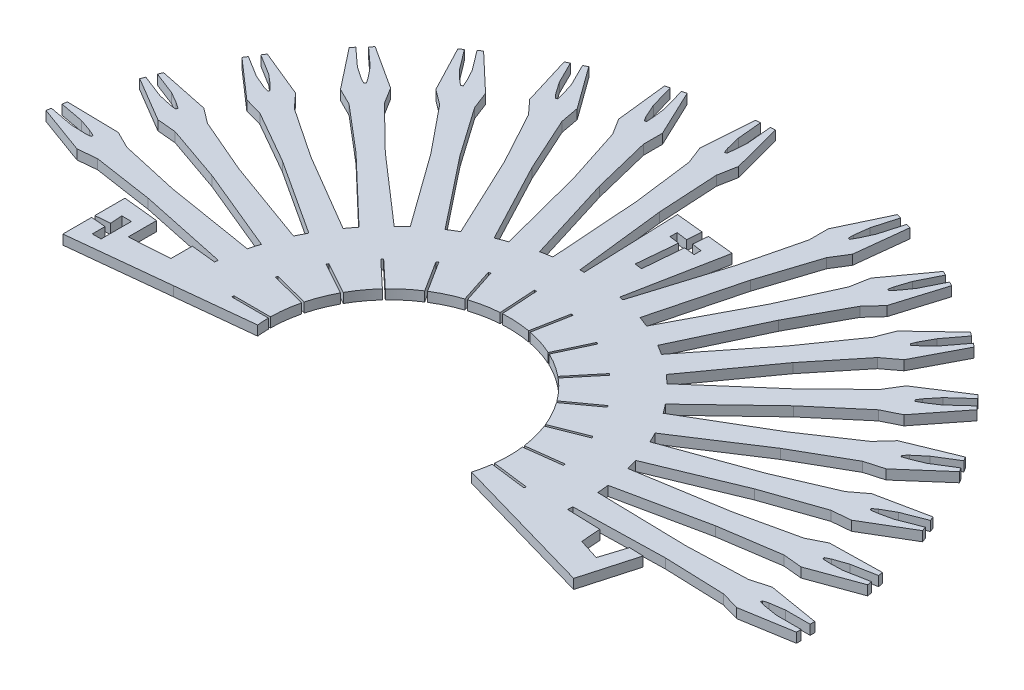
SolidWorks part; units mm, degrees
ref_plane "Front Plane" through (0, 0, 0) normal (0, 0, 1) x (1, 0, 0)
ref_plane "Top Plane" through (0, 0, 0) normal (0, 1, 0) x (1, 0, 0)
ref_plane "Right Plane" through (0, 0, 0) normal (1, 0, 0) x (0, 0, -1)
sketch "Sketch1" plane through (0, 0, 0) normal (0, 1, 0) x (1, 0, 0)
  line L5558 (72.849, 49.9) -> (72.743, 47.748) construction
  line L5559 (72.743, 47.748) -> (72.425, 45.667) construction
  line L5560 (72.425, 45.667) -> (71.896, 43.656) construction
  line L5561 (71.896, 43.656) -> (71.208, 41.716) construction
  line L5562 (71.208, 41.716) -> (70.309, 39.899) construction
  line L5563 (70.309, 39.899) -> (69.286, 38.171) construction
  line L5564 (69.286, 38.171) -> (66.71, 35.048) construction
  line L5565 (66.71, 35.048) -> (63.588, 32.491) construction
  line L5566 (63.588, 32.491) -> (61.877, 31.45) construction
  line L5567 (61.877, 31.45) -> (60.043, 30.551) construction
  line L5568 (60.043, 30.551) -> (58.12, 29.863) construction
  line L5569 (58.12, 29.863) -> (56.109, 29.333) construction
  line L5570 (56.109, 29.333) -> (54.01, 29.016) construction
  line L5571 (54.01, 29.016) -> (51.876, 28.91) construction
  line L5572 (51.876, 28.91) -> (49.724, 29.016) construction
  line L5573 (49.724, 29.016) -> (47.643, 29.333) construction
  line L5574 (47.643, 29.333) -> (45.632, 29.863) construction
  line L5575 (45.632, 29.863) -> (43.692, 30.551) construction
  line L5576 (43.692, 30.551) -> (41.839, 31.45) construction
  line L5577 (41.839, 31.45) -> (40.128, 32.491) construction
  line L5578 (40.128, 32.491) -> (37.006, 35.048) construction
  line L5579 (37.006, 35.048) -> (34.431, 38.171) construction
  line L5580 (34.431, 38.171) -> (33.408, 39.899) construction
  line L5581 (33.408, 39.899) -> (32.508, 41.716) construction
  line L5582 (32.508, 41.716) -> (31.821, 43.656) construction
  line L5583 (31.821, 43.656) -> (31.291, 45.667) construction
  line L5584 (31.291, 45.667) -> (30.974, 47.748) construction
  line L5585 (30.974, 47.748) -> (30.868, 49.9) construction
  line L5586 (30.868, 49.9) -> (30.974, 52.035) construction
  line L5587 (30.974, 52.035) -> (31.291, 54.134) construction
  line L5588 (31.291, 54.134) -> (31.821, 56.145) construction
  line L5589 (31.821, 56.145) -> (32.508, 58.067) construction
  line L5590 (32.508, 58.067) -> (33.408, 59.919) construction
  line L5591 (33.408, 59.919) -> (34.431, 61.648) construction
  line L5592 (34.431, 61.648) -> (37.006, 64.77) construction
  line L5593 (37.006, 64.77) -> (40.128, 67.328) construction
  line L5594 (40.128, 67.328) -> (41.839, 68.368) construction
  line L5595 (41.839, 68.368) -> (43.692, 69.268) construction
  line L5596 (43.692, 69.268) -> (45.632, 69.956) construction
  line L5597 (45.632, 69.956) -> (47.643, 70.485) construction
  line L5598 (47.643, 70.485) -> (49.724, 70.803) construction
  line L5599 (49.724, 70.803) -> (51.876, 70.908) construction
  line L5600 (51.876, 70.908) -> (54.01, 70.803) construction
  line L5601 (54.01, 70.803) -> (56.109, 70.485) construction
  line L5602 (56.109, 70.485) -> (58.12, 69.956) construction
  line L5603 (58.12, 69.956) -> (60.043, 69.268) construction
  line L5604 (60.043, 69.268) -> (61.877, 68.368) construction
  line L5605 (61.877, 68.368) -> (63.588, 67.328) construction
  line L5606 (63.588, 67.328) -> (66.71, 64.77) construction
  line L5607 (66.71, 64.77) -> (69.286, 61.648) construction
  line L5608 (69.286, 61.648) -> (70.309, 59.919) construction
  line L5609 (70.309, 59.919) -> (71.208, 58.067) construction
  line L5610 (71.208, 58.067) -> (71.896, 56.145) construction
  line L5611 (71.896, 56.145) -> (72.425, 54.134) construction
  line L5612 (72.425, 54.134) -> (72.743, 52.035) construction
  line L5613 (72.743, 52.035) -> (72.849, 49.9) construction
  line L5614 (62.054, 49.9) -> (61.842, 47.854) construction
  line L5615 (61.842, 47.854) -> (61.26, 45.932) construction
  line L5616 (61.26, 45.932) -> (60.307, 44.203) construction
  line L5617 (60.307, 44.203) -> (59.055, 42.704) construction
  line L5618 (59.055, 42.704) -> (57.556, 41.451) construction
  line L5619 (57.556, 41.451) -> (55.827, 40.499) construction
  line L5620 (55.827, 40.499) -> (53.922, 39.917) construction
  line L5621 (53.922, 39.917) -> (51.858, 39.705) construction
  line L5622 (51.858, 39.705) -> (49.795, 39.917) construction
  line L5623 (49.795, 39.917) -> (47.89, 40.499) construction
  line L5624 (47.89, 40.499) -> (46.143, 41.451) construction
  line L5625 (46.143, 41.451) -> (44.644, 42.704) construction
  line L5626 (44.644, 42.704) -> (43.392, 44.203) construction
  line L5627 (43.392, 44.203) -> (42.439, 45.932) construction
  line L5628 (42.439, 45.932) -> (41.857, 47.854) construction
  line L5629 (41.857, 47.854) -> (41.645, 49.9) construction
  line L5630 (41.645, 49.9) -> (41.857, 51.964) construction
  line L5631 (41.857, 51.964) -> (42.439, 53.869) construction
  line L5632 (42.439, 53.869) -> (43.392, 55.615) construction
  line L5633 (43.392, 55.615) -> (44.644, 57.115) construction
  line L5634 (44.644, 57.115) -> (46.143, 58.367) construction
  line L5635 (46.143, 58.367) -> (47.89, 59.32) construction
  line L5636 (47.89, 59.32) -> (49.795, 59.902) construction
  line L5637 (49.795, 59.902) -> (51.858, 60.113) construction
  line L5638 (51.858, 60.113) -> (53.922, 59.902) construction
  line L5639 (53.922, 59.902) -> (55.827, 59.32) construction
  line L5640 (55.827, 59.32) -> (57.556, 58.367) construction
  line L5641 (57.556, 58.367) -> (59.055, 57.115) construction
  line L5642 (59.055, 57.115) -> (60.307, 55.615) construction
  line L5643 (60.307, 55.615) -> (61.26, 53.869) construction
  line L5644 (61.26, 53.869) -> (61.842, 51.964) construction
  line L5645 (61.842, 51.964) -> (62.054, 49.9) construction
  line L5646 (30.85, 49.9) -> (51.841, 49.9) construction
  line L5647 (53.675, 70.82) -> (51.841, 49.9) construction
  line L5648 (72.531, 46.249) -> (51.858, 49.9) construction
  line L5649 (72.796, 48.436) -> (51.841, 49.9) construction
  line L5650 (51.488, 70.891) -> (51.841, 49.9) construction
  line L5651 (55.862, 70.52) -> (51.858, 49.9) construction
  line L5652 (30.956, 47.696) -> (51.841, 49.9) construction
  line L5653 (30.956, 52.088) -> (51.841, 49.9) construction
  line L5654 (72.037, 44.115) -> (51.841, 49.9) construction
  line L5655 (62.406, 49.177) -> (67.045, 49.424) construction
  line L5656 (67.345, 50.077) -> (67.469, 50.324) construction
  line L5657 (67.469, 50.324) -> (67.68, 50.377) construction
  line L5658 (67.68, 50.377) -> (67.892, 50.271) construction
  line L5659 (67.892, 50.271) -> (67.945, 50.059) construction
  line L5660 (67.945, 50.059) -> (67.839, 49.848) construction
  line L5661 (67.839, 49.848) -> (67.628, 49.759) construction
  line L5662 (67.628, 49.759) -> (67.416, 49.865) construction
  line L5663 (67.416, 49.865) -> (67.345, 50.077) construction
  line L5664 (69.832, 50.094) -> (69.938, 50.341) construction
  line L5665 (69.938, 50.341) -> (70.168, 50.394) construction
  line L5666 (70.168, 50.394) -> (70.379, 50.288) construction
  line L5667 (70.379, 50.288) -> (70.432, 50.077) construction
  line L5668 (70.432, 50.077) -> (70.326, 49.865) construction
  line L5669 (70.326, 49.865) -> (70.115, 49.777) construction
  line L5670 (70.115, 49.777) -> (69.903, 49.883) construction
  line L5671 (69.903, 49.883) -> (69.832, 50.094) construction
  line L5672 (67.045, 49.424) -> (71.702, 49.477) construction
  line L5673 (71.914, 50.094) -> (71.702, 49.477) construction
  line L5674 (62.389, 50.835) -> (67.045, 50.659) construction
  line L5675 (67.045, 50.659) -> (71.702, 50.712) construction
  line L5676 (71.914, 50.094) -> (71.702, 50.712) construction
  line L5677 (70.132, 50.377) -> (67.645, 50.359) construction
  line L5678 (70.15, 49.777) -> (67.645, 49.742) construction
  line L5679 (57.344, 49.953) -> (51.841, 49.9) construction
  line L5680 (62.353, 51.118) -> (66.887, 52.229) construction
  line L5681 (67.045, 52.917) -> (67.345, 53.252) construction
  line L5682 (67.345, 53.252) -> (67.557, 53.199) construction
  line L5683 (67.557, 53.199) -> (67.663, 52.987) construction
  line L5684 (67.663, 52.987) -> (67.61, 52.776) construction
  line L5685 (67.61, 52.776) -> (67.398, 52.652) construction
  line L5686 (67.398, 52.652) -> (67.187, 52.723) construction
  line L5687 (67.187, 52.723) -> (67.045, 52.917) construction
  line L5688 (69.48, 53.393) -> (69.779, 53.746) construction
  line L5689 (69.779, 53.746) -> (69.991, 53.693) construction
  line L5690 (69.991, 53.693) -> (70.097, 53.481) construction
  line L5691 (70.097, 53.481) -> (70.044, 53.269) construction
  line L5692 (70.044, 53.269) -> (69.832, 53.128) construction
  line L5693 (69.832, 53.128) -> (69.621, 53.217) construction
  line L5694 (69.621, 53.217) -> (69.48, 53.393) construction
  line L5695 (66.887, 52.229) -> (71.455, 53.128) construction
  line L5696 (71.543, 53.763) -> (71.455, 53.128) construction
  line L5697 (62.036, 52.758) -> (66.64, 53.428) construction
  line L5698 (66.64, 53.428) -> (71.208, 54.328) construction
  line L5699 (71.543, 53.781) -> (71.208, 54.328) construction
  line L5700 (69.744, 53.728) -> (67.292, 53.252) construction
  line L5701 (69.85, 53.128) -> (67.416, 52.634) construction
  line L5702 (57.238, 50.959) -> (51.841, 49.9) construction
  line L5703 (61.965, 53.023) -> (66.199, 54.945) construction
  line L5704 (66.234, 55.651) -> (66.446, 56.039) construction
  line L5705 (66.446, 56.039) -> (66.693, 56.021) construction
  line L5706 (66.693, 56.021) -> (66.851, 55.827) construction
  line L5707 (66.851, 55.827) -> (66.64, 55.457) construction
  line L5708 (66.64, 55.457) -> (66.393, 55.492) construction
  line L5709 (66.393, 55.492) -> (66.234, 55.651) construction
  line L5710 (68.545, 56.568) -> (68.756, 56.956) construction
  line L5711 (68.756, 56.956) -> (69.003, 56.938) construction
  line L5712 (69.003, 56.938) -> (69.162, 56.744) construction
  line L5713 (69.162, 56.744) -> (68.95, 56.374) construction
  line L5714 (68.95, 56.374) -> (68.703, 56.409) construction
  line L5715 (68.703, 56.409) -> (68.545, 56.568) construction
  line L5716 (66.199, 54.945) -> (70.52, 56.656) construction
  line L5717 (70.503, 57.309) -> (70.52, 56.656) construction
  line L5718 (61.348, 54.575) -> (65.74, 56.092) construction
  line L5719 (65.74, 56.092) -> (70.079, 57.803) construction
  line L5720 (70.503, 57.309) -> (70.079, 57.803) construction
  line L5721 (68.739, 56.938) -> (66.41, 56.021) construction
  line L5722 (68.968, 56.374) -> (66.64, 55.439) construction
  line L5723 (56.956, 51.929) -> (51.841, 49.9) construction
  line L5724 (61.225, 54.822) -> (65.035, 57.485) construction
  line L5725 (64.946, 58.191) -> (65.07, 58.614) construction
  line L5726 (65.07, 58.614) -> (65.317, 58.632) construction
  line L5727 (65.317, 58.632) -> (65.493, 58.473) construction
  line L5728 (65.493, 58.473) -> (65.528, 58.244) construction
  line L5729 (65.528, 58.244) -> (65.37, 58.05) construction
  line L5730 (65.37, 58.05) -> (64.946, 58.191) construction
  line L5731 (67.045, 59.514) -> (67.169, 59.937) construction
  line L5732 (67.169, 59.937) -> (67.416, 59.955) construction
  line L5733 (67.416, 59.955) -> (67.592, 59.796) construction
  line L5734 (67.592, 59.796) -> (67.628, 59.567) construction
  line L5735 (67.628, 59.567) -> (67.469, 59.373) construction
  line L5736 (67.469, 59.373) -> (67.045, 59.514) construction
  line L5737 (65.035, 57.485) -> (68.968, 59.972) construction
  line L5738 (68.827, 60.607) -> (68.968, 59.972) construction
  line L5739 (60.325, 56.233) -> (64.382, 58.526) construction
  line L5740 (64.382, 58.526) -> (68.315, 61.013) construction
  line L5741 (68.827, 60.607) -> (68.315, 61.013) construction
  line L5742 (67.169, 59.919) -> (65.052, 58.579) construction
  line L5743 (67.486, 59.39) -> (65.37, 58.067) construction
  line L5744 (56.497, 52.828) -> (51.858, 49.9) construction
  line L5745 (60.149, 56.444) -> (63.429, 59.761) construction
  line L5746 (63.2, 60.448) -> (63.147, 60.678) construction
  line L5747 (63.147, 60.678) -> (63.288, 60.889) construction
  line L5748 (63.288, 60.889) -> (63.5, 60.942) construction
  line L5749 (63.5, 60.942) -> (63.712, 60.837) construction
  line L5750 (63.712, 60.837) -> (63.765, 60.607) construction
  line L5751 (63.765, 60.607) -> (63.659, 60.396) construction
  line L5752 (63.659, 60.396) -> (63.412, 60.343) construction
  line L5753 (63.412, 60.343) -> (63.2, 60.448) construction
  line L5754 (65.017, 62.124) -> (64.964, 62.371) construction
  line L5755 (64.964, 62.371) -> (65.105, 62.583) construction
  line L5756 (65.105, 62.583) -> (65.317, 62.636) construction
  line L5757 (65.317, 62.636) -> (65.528, 62.53) construction
  line L5758 (65.528, 62.53) -> (65.581, 62.283) construction
  line L5759 (65.581, 62.283) -> (65.476, 62.071) construction
  line L5760 (65.476, 62.071) -> (65.229, 62.018) construction
  line L5761 (65.229, 62.018) -> (65.017, 62.124) construction
  line L5762 (63.429, 59.761) -> (66.834, 62.936) construction
  line L5763 (66.587, 63.535) -> (66.834, 62.936) construction
  line L5764 (59.02, 57.679) -> (62.583, 60.678) construction
  line L5765 (62.583, 60.678) -> (66.005, 63.835) construction
  line L5766 (66.587, 63.535) -> (66.005, 63.835) construction
  line L5767 (65.07, 62.548) -> (63.235, 60.854) construction
  line L5768 (65.493, 62.089) -> (63.659, 60.396) construction
  line L5769 (55.88, 53.622) -> (51.841, 49.9) construction
  line L5770 (58.808, 57.873) -> (61.419, 61.718) construction
  line L5771 (61.083, 62.353) -> (60.995, 62.583) construction
  line L5772 (60.995, 62.583) -> (61.083, 62.794) construction
  line L5773 (61.083, 62.794) -> (61.295, 62.9) construction
  line L5774 (61.295, 62.9) -> (61.507, 62.83) construction
  line L5775 (61.507, 62.83) -> (61.613, 62.618) construction
  line L5776 (61.613, 62.618) -> (61.524, 62.371) construction
  line L5777 (61.524, 62.371) -> (61.313, 62.301) construction
  line L5778 (61.313, 62.301) -> (61.083, 62.353) construction
  line L5779 (62.565, 64.329) -> (62.477, 64.576) construction
  line L5780 (62.477, 64.576) -> (62.565, 64.788) construction
  line L5781 (62.565, 64.788) -> (62.777, 64.893) construction
  line L5782 (62.777, 64.893) -> (62.988, 64.805) construction
  line L5783 (62.988, 64.805) -> (63.094, 64.594) construction
  line L5784 (63.094, 64.594) -> (63.006, 64.364) construction
  line L5785 (63.006, 64.364) -> (62.794, 64.276) construction
  line L5786 (62.794, 64.276) -> (62.565, 64.329) construction
  line L5787 (61.419, 61.718) -> (64.206, 65.458) construction
  line L5788 (63.835, 66.005) -> (64.206, 65.458) construction
  line L5789 (57.485, 58.861) -> (60.431, 62.459) construction
  line L5790 (60.431, 62.459) -> (63.2, 66.199) construction
  line L5791 (63.835, 66.005) -> (63.2, 66.199) construction
  line L5792 (62.53, 64.752) -> (61.031, 62.759) construction
  line L5793 (63.024, 64.382) -> (61.524, 62.389) construction
  line L5794 (55.122, 54.31) -> (51.858, 49.9) construction
  line L5795 (57.238, 59.002) -> (59.09, 63.271) construction
  line L5796 (58.649, 63.835) -> (58.508, 64.047) construction
  line L5797 (58.508, 64.047) -> (58.561, 64.258) construction
  line L5798 (58.561, 64.258) -> (58.755, 64.417) construction
  line L5799 (58.755, 64.417) -> (58.967, 64.364) construction
  line L5800 (58.967, 64.364) -> (59.126, 64.17) construction
  line L5801 (59.126, 64.17) -> (59.073, 63.941) construction
  line L5802 (59.073, 63.941) -> (58.879, 63.8) construction
  line L5803 (58.879, 63.8) -> (58.649, 63.835) construction
  line L5804 (59.743, 66.058) -> (59.602, 66.269) construction
  line L5805 (59.602, 66.269) -> (59.655, 66.481) construction
  line L5806 (59.655, 66.481) -> (59.849, 66.604) construction
  line L5807 (59.849, 66.604) -> (60.06, 66.587) construction
  line L5808 (60.06, 66.587) -> (60.219, 66.393) construction
  line L5809 (60.219, 66.393) -> (60.166, 66.163) construction
  line L5810 (60.166, 66.163) -> (59.972, 66.022) construction
  line L5811 (59.972, 66.022) -> (59.743, 66.058) construction
  line L5812 (59.09, 63.271) -> (61.136, 67.451) construction
  line L5813 (60.695, 67.927) -> (61.136, 67.451) construction
  line L5814 (55.739, 59.743) -> (57.979, 63.818) construction
  line L5815 (57.979, 63.818) -> (60.025, 67.998) construction
  line L5816 (60.678, 67.927) -> (60.025, 67.998) construction
  line L5817 (59.619, 66.463) -> (58.526, 64.223) construction
  line L5818 (60.184, 66.181) -> (59.073, 63.941) construction
  line L5819 (54.257, 54.822) -> (51.841, 49.9) construction
  line L5820 (55.457, 59.849) -> (56.497, 64.382) construction
  line L5821 (55.951, 64.841) -> (55.792, 64.999) construction
  line L5822 (55.792, 64.999) -> (55.792, 65.246) construction
  line L5823 (55.792, 65.246) -> (55.951, 65.423) construction
  line L5824 (55.951, 65.423) -> (56.18, 65.423) construction
  line L5825 (56.18, 65.423) -> (56.339, 65.264) construction
  line L5826 (56.339, 65.264) -> (56.339, 65.035) construction
  line L5827 (56.339, 65.035) -> (56.18, 64.876) construction
  line L5828 (56.18, 64.876) -> (55.951, 64.841) construction
  line L5829 (56.603, 67.239) -> (56.444, 67.398) construction
  line L5830 (56.444, 67.398) -> (56.444, 67.628) construction
  line L5831 (56.444, 67.628) -> (56.603, 67.822) construction
  line L5832 (56.603, 67.822) -> (56.85, 67.822) construction
  line L5833 (56.85, 67.822) -> (57.009, 67.663) construction
  line L5834 (57.009, 67.663) -> (57.009, 67.416) construction
  line L5835 (57.009, 67.416) -> (56.85, 67.257) construction
  line L5836 (56.85, 67.257) -> (56.603, 67.239) construction
  line L5837 (56.497, 64.382) -> (57.732, 68.88) construction
  line L5838 (57.203, 69.25) -> (57.732, 68.88) construction
  line L5839 (53.852, 60.29) -> (55.298, 64.717) construction
  line L5840 (55.298, 64.717) -> (56.533, 69.197) construction
  line L5841 (57.185, 69.25) -> (56.533, 69.197) construction
  line L5842 (56.427, 67.61) -> (55.757, 65.211) construction
  line L5843 (57.009, 67.451) -> (56.356, 65.035) construction
  line L5844 (53.305, 55.192) -> (51.841, 49.9) construction
  line L5845 (51.664, 60.484) -> (50.994, 65.088) construction
  line L5846 (50.324, 65.317) -> (50.112, 65.423) construction
  line L5847 (50.112, 65.423) -> (50.024, 65.634) construction
  line L5848 (50.024, 65.634) -> (50.112, 65.846) construction
  line L5849 (50.112, 65.846) -> (50.324, 65.952) construction
  line L5850 (50.324, 65.952) -> (50.553, 65.846) construction
  line L5851 (50.553, 65.846) -> (50.641, 65.634) construction
  line L5852 (50.641, 65.634) -> (50.553, 65.423) construction
  line L5853 (50.553, 65.423) -> (50.324, 65.317) construction
  line L5854 (50.077, 67.786) -> (49.865, 67.892) construction
  line L5855 (49.865, 67.892) -> (49.795, 68.104) construction
  line L5856 (49.795, 68.104) -> (49.865, 68.315) construction
  line L5857 (49.865, 68.315) -> (50.077, 68.421) construction
  line L5858 (50.077, 68.421) -> (50.324, 68.315) construction
  line L5859 (50.324, 68.315) -> (50.394, 68.104) construction
  line L5860 (50.394, 68.104) -> (50.324, 67.892) construction
  line L5861 (50.324, 67.892) -> (50.077, 67.786) construction
  line L5862 (50.994, 65.088) -> (50.535, 69.727) construction
  line L5863 (49.918, 69.885) -> (50.535, 69.727) construction
  line L5864 (50.006, 60.325) -> (49.759, 64.964) construction
  line L5865 (49.759, 64.964) -> (49.318, 69.603) construction
  line L5866 (49.9, 69.885) -> (49.318, 69.603) construction
  line L5867 (49.777, 68.068) -> (50.024, 65.599) construction
  line L5868 (50.377, 68.139) -> (50.624, 65.652) construction
  line L5869 (51.312, 55.368) -> (51.858, 49.9) construction
  line L5870 (49.724, 60.272) -> (48.225, 64.664) construction
  line L5871 (47.519, 64.788) -> (47.308, 64.841) construction
  line L5872 (47.308, 64.841) -> (47.184, 65.052) construction
  line L5873 (47.184, 65.052) -> (47.237, 65.264) construction
  line L5874 (47.237, 65.264) -> (47.413, 65.387) construction
  line L5875 (47.413, 65.387) -> (47.66, 65.334) construction
  line L5876 (47.66, 65.334) -> (47.784, 65.158) construction
  line L5877 (47.784, 65.158) -> (47.731, 64.946) construction
  line L5878 (47.731, 64.946) -> (47.519, 64.788) construction
  line L5879 (46.831, 67.169) -> (46.62, 67.222) construction
  line L5880 (46.62, 67.222) -> (46.496, 67.433) construction
  line L5881 (46.496, 67.433) -> (46.549, 67.645) construction
  line L5882 (46.549, 67.645) -> (46.725, 67.769) construction
  line L5883 (46.725, 67.769) -> (46.972, 67.716) construction
  line L5884 (46.972, 67.716) -> (47.096, 67.539) construction
  line L5885 (47.096, 67.539) -> (47.043, 67.328) construction
  line L5886 (47.043, 67.328) -> (46.831, 67.169) construction
  line L5887 (48.225, 64.664) -> (46.937, 69.144) construction
  line L5888 (46.284, 69.18) -> (46.937, 69.144) construction
  line L5889 (48.119, 59.796) -> (47.043, 64.329) construction
  line L5890 (47.043, 64.329) -> (45.738, 68.809) construction
  line L5891 (46.267, 69.18) -> (45.738, 68.792) construction
  line L5892 (46.478, 67.381) -> (47.166, 64.982) construction
  line L5893 (47.061, 67.557) -> (47.766, 65.158) construction
  line L5894 (50.324, 55.174) -> (51.841, 49.9) construction
  line L5895 (47.854, 59.708) -> (45.579, 63.747) construction
  line L5896 (44.873, 63.729) -> (44.662, 63.765) construction
  line L5897 (44.662, 63.765) -> (44.503, 63.923) construction
  line L5898 (44.503, 63.923) -> (44.503, 64.153) construction
  line L5899 (44.503, 64.153) -> (44.662, 64.311) construction
  line L5900 (44.662, 64.311) -> (44.891, 64.311) construction
  line L5901 (44.891, 64.311) -> (45.05, 64.135) construction
  line L5902 (45.05, 64.135) -> (45.05, 63.923) construction
  line L5903 (45.05, 63.923) -> (44.873, 63.729) construction
  line L5904 (43.762, 65.952) -> (43.55, 65.969) construction
  line L5905 (43.55, 65.969) -> (43.356, 66.128) construction
  line L5906 (43.356, 66.128) -> (43.392, 66.375) construction
  line L5907 (43.392, 66.375) -> (43.55, 66.534) construction
  line L5908 (43.55, 66.534) -> (43.78, 66.534) construction
  line L5909 (43.78, 66.534) -> (43.938, 66.34) construction
  line L5910 (43.938, 66.34) -> (43.938, 66.128) construction
  line L5911 (43.938, 66.128) -> (43.762, 65.952) construction
  line L5912 (45.579, 63.747) -> (43.498, 67.91) construction
  line L5913 (42.845, 67.839) -> (43.498, 67.91) construction
  line L5914 (46.373, 58.949) -> (44.485, 63.2) construction
  line L5915 (44.485, 63.2) -> (42.386, 67.363) construction
  line L5916 (42.827, 67.839) -> (42.386, 67.363) construction
  line L5917 (43.374, 66.111) -> (44.485, 63.87) construction
  line L5918 (43.921, 66.393) -> (45.032, 64.153) construction
  line L5919 (49.389, 54.804) -> (51.841, 49.9) construction
  line L5920 (46.126, 58.808) -> (43.145, 62.371) construction
  line L5921 (42.457, 62.23) -> (42.245, 62.195) construction
  line L5922 (42.245, 62.195) -> (42.051, 62.336) construction
  line L5923 (42.051, 62.336) -> (41.998, 62.565) construction
  line L5924 (41.998, 62.565) -> (42.139, 62.759) construction
  line L5925 (42.139, 62.759) -> (42.369, 62.777) construction
  line L5926 (42.369, 62.777) -> (42.563, 62.653) construction
  line L5927 (42.563, 62.653) -> (42.58, 62.442) construction
  line L5928 (42.58, 62.442) -> (42.457, 62.23) construction
  line L5929 (40.958, 64.188) -> (40.746, 64.17) construction
  line L5930 (40.746, 64.17) -> (40.552, 64.294) construction
  line L5931 (40.552, 64.294) -> (40.499, 64.541) construction
  line L5932 (40.499, 64.541) -> (40.64, 64.717) construction
  line L5933 (40.64, 64.717) -> (40.869, 64.752) construction
  line L5934 (40.869, 64.752) -> (41.063, 64.611) construction
  line L5935 (41.063, 64.611) -> (41.081, 64.4) construction
  line L5936 (41.081, 64.4) -> (40.958, 64.188) construction
  line L5937 (43.145, 62.371) -> (40.323, 66.075) construction
  line L5938 (39.705, 65.881) -> (40.323, 66.075) construction
  line L5939 (44.803, 57.803) -> (42.157, 61.63) construction
  line L5940 (42.157, 61.63) -> (39.352, 65.334) construction
  line L5941 (39.705, 65.881) -> (39.352, 65.334) construction
  line L5942 (40.534, 64.276) -> (42.051, 62.301) construction
  line L5943 (41.028, 64.647) -> (42.545, 62.671) construction
  line L5944 (48.525, 54.275) -> (51.858, 49.9) construction
  line L5945 (44.591, 57.609) -> (41.01, 60.572) construction
  line L5946 (40.358, 60.29) -> (40.146, 60.219) construction
  line L5947 (40.146, 60.219) -> (39.934, 60.325) construction
  line L5948 (39.934, 60.325) -> (39.846, 60.537) construction
  line L5949 (39.846, 60.537) -> (39.952, 60.748) construction
  line L5950 (39.952, 60.748) -> (40.164, 60.819) construction
  line L5951 (40.164, 60.819) -> (40.375, 60.748) construction
  line L5952 (40.375, 60.748) -> (40.464, 60.537) construction
  line L5953 (40.464, 60.537) -> (40.358, 60.29) construction
  line L5954 (38.523, 61.965) -> (38.312, 61.877) construction
  line L5955 (38.312, 61.877) -> (38.1, 61.983) construction
  line L5956 (38.1, 61.983) -> (38.012, 62.195) construction
  line L5957 (38.012, 62.195) -> (38.118, 62.406) construction
  line L5958 (38.118, 62.406) -> (38.329, 62.495) construction
  line L5959 (38.329, 62.495) -> (38.541, 62.406) construction
  line L5960 (38.541, 62.406) -> (38.629, 62.195) construction
  line L5961 (38.629, 62.195) -> (38.523, 61.965) construction
  line L5962 (41.01, 60.572) -> (37.553, 63.694) construction
  line L5963 (36.989, 63.394) -> (37.553, 63.694) construction
  line L5964 (43.48, 56.374) -> (40.181, 59.655) construction
  line L5965 (40.181, 59.655) -> (36.724, 62.777) construction
  line L5966 (36.971, 63.377) -> (36.724, 62.777) construction
  line L5967 (38.1, 61.965) -> (39.952, 60.29) construction
  line L5968 (38.506, 62.424) -> (40.358, 60.748) construction
  line L5969 (47.784, 53.587) -> (51.841, 49.9) construction
  line L5970 (43.303, 56.145) -> (39.247, 58.402) construction
  line L5971 (38.647, 58.014) -> (38.453, 57.908) construction
  line L5972 (38.453, 57.908) -> (38.223, 57.961) construction
  line L5973 (38.223, 57.961) -> (38.118, 58.173) construction
  line L5974 (38.118, 58.173) -> (38.171, 58.385) construction
  line L5975 (38.171, 58.385) -> (38.594, 58.455) construction
  line L5976 (38.594, 58.455) -> (38.7, 58.244) construction
  line L5977 (38.7, 58.244) -> (38.647, 58.014) construction
  line L5978 (36.53, 59.32) -> (36.354, 59.214) construction
  line L5979 (36.354, 59.214) -> (36.107, 59.267) construction
  line L5980 (36.107, 59.267) -> (36.001, 59.478) construction
  line L5981 (36.001, 59.478) -> (36.054, 59.69) construction
  line L5982 (36.054, 59.69) -> (36.477, 59.761) construction
  line L5983 (36.477, 59.761) -> (36.583, 59.549) construction
  line L5984 (36.583, 59.549) -> (36.53, 59.32) construction
  line L5985 (39.247, 58.402) -> (35.278, 60.854) construction
  line L5986 (34.766, 60.448) -> (35.278, 60.837) construction
  line L5987 (42.439, 54.733) -> (38.594, 57.344) construction
  line L5988 (38.594, 57.344) -> (34.625, 59.796) construction
  line L5989 (34.766, 60.431) -> (34.625, 59.796) construction
  line L5990 (36.124, 59.249) -> (38.241, 57.926) construction
  line L5991 (36.442, 59.761) -> (38.559, 58.455) construction
  line L5992 (47.184, 52.776) -> (51.841, 49.9) construction
  line L5993 (42.316, 54.469) -> (37.888, 55.951) construction
  line L5994 (37.377, 55.457) -> (37.218, 55.316) construction
  line L5995 (37.218, 55.316) -> (36.989, 55.316) construction
  line L5996 (36.989, 55.316) -> (36.83, 55.51) construction
  line L5997 (36.83, 55.51) -> (36.848, 55.739) construction
  line L5998 (36.848, 55.739) -> (37.006, 55.898) construction
  line L5999 (37.006, 55.898) -> (37.253, 55.88) construction
  line L6000 (37.253, 55.88) -> (37.412, 55.686) construction
  line L6001 (37.412, 55.686) -> (37.377, 55.457) construction
  line L6002 (35.066, 56.356) -> (34.907, 56.215) construction
  line L6003 (34.907, 56.215) -> (34.678, 56.215) construction
  line L6004 (34.678, 56.215) -> (34.519, 56.409) construction
  line L6005 (34.519, 56.409) -> (34.537, 56.638) construction
  line L6006 (34.537, 56.638) -> (34.696, 56.797) construction
  line L6007 (34.696, 56.797) -> (34.943, 56.78) construction
  line L6008 (34.943, 56.78) -> (35.101, 56.586) construction
  line L6009 (35.101, 56.586) -> (35.066, 56.356) construction
  line L6010 (37.888, 55.951) -> (33.549, 57.626) construction
  line L6011 (33.126, 57.132) -> (33.549, 57.626) construction
  line L6012 (41.716, 52.917) -> (37.447, 54.804) construction
  line L6013 (37.447, 54.804) -> (33.108, 56.48) construction
  line L6014 (33.126, 57.132) -> (33.108, 56.48) construction
  line L6015 (34.678, 56.198) -> (37.006, 55.298) construction
  line L6016 (34.89, 56.78) -> (37.218, 55.88) construction
  line L6017 (46.725, 51.876) -> (51.858, 49.9) construction
  line L6018 (41.628, 52.652) -> (37.024, 53.287) construction
  line L6019 (36.601, 52.705) -> (36.477, 52.529) construction
  line L6020 (36.477, 52.529) -> (36.23, 52.493) construction
  line L6021 (36.23, 52.493) -> (36.054, 52.652) construction
  line L6022 (36.054, 52.652) -> (36.019, 52.899) construction
  line L6023 (36.019, 52.899) -> (36.389, 53.111) construction
  line L6024 (36.389, 53.111) -> (36.583, 52.952) construction
  line L6025 (36.583, 52.952) -> (36.601, 52.705) construction
  line L6026 (34.167, 53.164) -> (34.043, 52.987) construction
  line L6027 (34.043, 52.987) -> (33.796, 52.952) construction
  line L6028 (33.796, 52.952) -> (33.62, 53.111) construction
  line L6029 (33.62, 53.111) -> (33.584, 53.358) construction
  line L6030 (33.584, 53.358) -> (33.955, 53.569) construction
  line L6031 (33.955, 53.569) -> (34.149, 53.411) construction
  line L6032 (34.149, 53.411) -> (34.167, 53.164) construction
  line L6033 (37.024, 53.287) -> (32.438, 54.134) construction
  line L6034 (32.12, 53.587) -> (32.438, 54.134) construction
  line L6035 (41.328, 51.012) -> (36.795, 52.07) construction
  line L6036 (36.795, 52.07) -> (32.226, 52.934) construction
  line L6037 (32.12, 53.569) -> (32.226, 52.934) construction
  line L6038 (33.814, 52.952) -> (36.266, 52.493) construction
  line L6039 (33.92, 53.552) -> (36.371, 53.093) construction
  line L6040 (46.461, 50.906) -> (51.858, 49.9) construction
  line L6041 (57.856, 49.9) -> (57.714, 48.683) construction
  line L6042 (57.714, 48.683) -> (57.379, 47.572) construction
  line L6043 (57.379, 47.572) -> (56.815, 46.567) construction
  line L6044 (56.815, 46.567) -> (56.109, 45.667) construction
  line L6045 (56.109, 45.667) -> (55.21, 44.944) construction
  line L6046 (55.21, 44.944) -> (54.204, 44.397) construction
  line L6047 (54.204, 44.397) -> (53.093, 44.044) construction
  line L6048 (53.093, 44.044) -> (51.876, 43.921) construction
  line L6049 (51.876, 43.921) -> (50.659, 44.044) construction
  line L6050 (50.659, 44.044) -> (49.512, 44.397) construction
  line L6051 (49.512, 44.397) -> (48.507, 44.944) construction
  line L6052 (48.507, 44.944) -> (47.607, 45.667) construction
  line L6053 (47.607, 45.667) -> (46.902, 46.567) construction
  line L6054 (46.902, 46.567) -> (46.337, 47.572) construction
  line L6055 (46.337, 47.572) -> (46.002, 48.683) construction
  line L6056 (46.002, 48.683) -> (45.861, 49.9) construction
  line L6057 (45.861, 49.9) -> (46.002, 51.118) construction
  line L6058 (46.002, 51.118) -> (46.337, 52.246) construction
  line L6059 (46.337, 52.246) -> (46.902, 53.252) construction
  line L6060 (46.902, 53.252) -> (47.607, 54.151) construction
  line L6061 (47.607, 54.151) -> (48.507, 54.875) construction
  line L6062 (48.507, 54.875) -> (49.512, 55.421) construction
  line L6063 (49.512, 55.421) -> (50.659, 55.774) construction
  line L6064 (50.659, 55.774) -> (51.876, 55.898) construction
  line L6065 (51.876, 55.898) -> (53.093, 55.774) construction
  line L6066 (53.093, 55.774) -> (54.204, 55.421) construction
  line L6067 (54.204, 55.421) -> (55.21, 54.875) construction
  line L6068 (55.21, 54.875) -> (56.109, 54.151) construction
  line L6069 (56.109, 54.151) -> (56.815, 53.252) construction
  line L6070 (56.815, 53.252) -> (57.379, 52.246) construction
  line L6071 (57.379, 52.246) -> (57.714, 51.118) construction
  line L6072 (57.714, 51.118) -> (57.856, 49.9) construction
sketch "Sketch2" plane through (0, 0, 0) normal (0, 1, 0) x (1, 0, 0)
  line L0 (41.7366, 50.9583) -> (36.5552, 51.5014)
  line L1 (51.841, 49.9) -> (53.163, 64.9033) construction
  line L2 (30.956, 52.088) -> (51.841, 49.9) construction
  line L3 (36.5552, 51.5014) -> (36.5552, 48.2869)
  line L4 (30.956, 47.696) -> (51.841, 49.9) construction
  line L5 (36.5552, 48.2869) -> (41.7327, 48.8337)
  line L7 (61.6124, 47.1011) -> (66.5007, 45.7008)
  line L8 (72.037, 44.115) -> (51.841, 49.9) construction
  line L9 (66.5007, 45.7008) -> (67.012, 48.8401)
  line L10 (72.796, 48.436) -> (51.841, 49.9) construction
  line L11 (67.012, 48.8401) -> (61.9609, 49.0012)
  line L12 (62.054, 49.9) -> (61.842, 47.854) construction
  line L13 (51.765, 60.0594) -> (51.586, 65.0642)
  line L14 (51.488, 70.891) -> (51.841, 49.9) construction
  line L15 (51.586, 65.0642) -> (54.7401, 64.7424)
  line L16 (55.862, 70.52) -> (51.858, 49.9) construction
  line L17 (54.7401, 64.7424) -> (53.794, 59.8702)
  circle A0 centre (51.841, 49.9) radius 6.2002
  arc A1 (61.9609, 49.0012) -> (53.794, 59.8702) centre (51.841, 49.9) ccw
  arc A2 (41.7375, 50.967) -> (41.7366, 50.9583) centre (51.841, 49.9) ccw
  arc A3 (41.7327, 48.8337) -> (41.7338, 48.8238) centre (51.841, 49.9) ccw
  arc A4 (41.7338, 48.8238) -> (61.6124, 47.1011) centre (51.841, 49.9) ccw
  arc A5 (51.765, 60.0594) -> (41.7375, 50.967) centre (51.841, 49.9) ccw
extrude "Boss-Extrude1" add sketch "Sketch2" along normal blind 0.5
sketch "Sketch3" plane through (0, 0, 0) normal (0, 1, 0) x (1, 0, 0)
  line L0 (34.0857, 50.3207) -> (32.7162, 50.6322) construction
  line L1 (30.85, 49.9) -> (51.841, 49.9) construction
  line L2 (41.7282, 50.4911) -> (37.2554, 50.2819) construction
  line L3 (32.7162, 50.6322) -> (32.323, 50.6098) construction
  line L4 (32.323, 50.6098) -> (30.1914, 50.3756) construction
  line L5 (30.1914, 50.3756) -> (30.1967, 50.3818) construction
  line L7 (37.2554, 50.2819) -> (34.0857, 50.3207) construction
  line L8 (30.9964, 50.2252) -> (31.0029, 50.2183) construction
  line L9 (30.8082, 50.2183) -> (31.0029, 50.2183) construction
  line L11 (41.7282, 50.4911) -> (41.7282, 49.4512) construction
  line L12 (31.194, 49.6753) -> (31.1199, 49.6329) construction
  line L13 (30.8082, 50.2183) -> (30.6431, 50.2183) construction
  line L14 (30.6431, 50.2183) -> (30.1967, 50.2521) construction
  line L15 (30.7788, 49.6329) -> (31.1199, 49.6329) construction
  line L16 (30.1967, 50.2521) -> (30.1967, 50.3818) construction
  line L17 (30.3951, 49.2413) -> (30.1967, 49.4512) construction
  line L18 (30.8191, 49.1966) -> (30.3951, 49.2413) construction
  line L19 (32.6688, 49.1966) -> (30.8191, 49.1966) construction
  line L20 (41.7282, 49.4512) -> (37.2554, 49.5186) construction
  line L21 (34.213, 49.341) -> (32.6688, 49.1966) construction
  line L22 (30.7788, 49.6329) -> (30.7516, 49.685) construction
  line L23 (30.7516, 49.685) -> (30.1967, 49.6405) construction
  line L24 (30.1967, 49.6405) -> (30.1967, 49.4512) construction
  line L25 (37.2554, 49.5186) -> (34.213, 49.341) construction
  line L26 (51.841, 49.9) -> (28.9127, 49.9) construction
  line L27 (32.2273, 50.0311) -> (31.5743, 50.1336)
  line L28 (30.2995, 50.1336) -> (30.2995, 50.3756)
  line L29 (30.2995, 50.3756) -> (32.9477, 50.8173)
  line L30 (32.9477, 50.8173) -> (33.8949, 50.5468)
  line L31 (33.8949, 50.5468) -> (37.0058, 50.4361)
  line L32 (37.0058, 50.4361) -> (41.8575, 50.5468)
  line L33 (41.8575, 50.5468) -> (41.8575, 49.2532)
  line L34 (32.2273, 50.0311) -> (32.5881, 49.9474)
  line L35 (32.5881, 49.9474) -> (32.5881, 49.8526)
  line L36 (31.5743, 50.1336) -> (30.2995, 50.1336)
  line L37 (37.0058, 49.3639) -> (41.8575, 49.2532)
  line L38 (33.8949, 49.2532) -> (37.0058, 49.3639)
  line L39 (32.9477, 48.9827) -> (33.8949, 49.2532)
  line L40 (30.2995, 49.4244) -> (32.9477, 48.9827)
  line L41 (31.5743, 49.6664) -> (30.2995, 49.6664)
  line L42 (30.2995, 49.6664) -> (30.2995, 49.4244)
  line L43 (32.323, 49.7782) -> (31.5743, 49.6664)
  line L44 (32.323, 49.7782) -> (32.5881, 49.8526)
  circle A0 centre (32.2123, 49.6) radius 0.1651 construction
  circle A1 centre (30.8082, 50.2183) radius 0.1651 construction
  circle A2 centre (32.2123, 49.9) radius 0.1814 construction
  circle A3 centre (32.2123, 50.1956) radius 0.1651 construction
  circle A4 centre (31.0611, 50.1336) radius 0.1651 construction
  arc A5 (31.1468, 50.2004) -> (30.9964, 50.2252) centre (31.1468, 50.6691) cw construction
  circle A6 centre (32.2123, 49.9) radius 0.3 construction
  arc A7 (31.4269, 49.7372) -> (31.194, 49.6753) centre (31.4269, 49.2685) ccw construction
  circle A8 centre (32.2204, 50.696) radius 0.1651 construction
  circle A9 centre (31.0427, 50.4996) radius 0.1651 construction
  circle A10 centre (31.1468, 50.9854) radius 0.1651 construction
  point P21 (41.7282, 49.9)
  point P54 (41.7282, 49.9)
  point P60 (41.8575, 49.9)
  point P68 (32.5881, 49.9)
extrude "Boss-Extrude2" add sketch "Sketch3" along normal blind 0.5
sketch "Sketch5" plane through (0, 0, 0) normal (0, 1, 0) x (1, 0, 0)
  line L0 (51.841, 49.9) -> (51.841, 47.986)
  line L1 (30.85, 49.9) -> (51.841, 49.9) construction
  line L2 (51.841, 49.9) -> (47.5187, 49.9)
  line L4 (47.5187, 49.9) -> (51.841, 47.986)
extrude "Boss-Extrude3" add sketch "Sketch5" along normal blind 0.5 separate body
pattern_circular "CirPattern1" count 18 over 180 about axis through (51.841, 0, -49.9) along (0, 1, 0) of "Boss-Extrude2"
sketch "Sketch8" plane through (0, 0, 0) normal (0, 1, 0) x (1, 0, 0)
  line L0 (36.5552, 48.2869) -> (27.9956, 47.1697)
  line L1 (27.9956, 47.1697) -> (27.9956, 52.8907)
  line L2 (27.9956, 52.8907) -> (36.5552, 51.5014)
  line L3 (36.5552, 51.5014) -> (36.5552, 48.754)
  line L5 (36.5552, 48.754) -> (36.5552, 48.2869)
  line L6 (51.6556, 72.5266) -> (51.586, 65.0642)
  line L7 (51.586, 65.0642) -> (54.7401, 64.7424)
  line L8 (54.7401, 64.7424) -> (56.407, 72.5266)
  line L9 (56.407, 72.5266) -> (51.6556, 72.5266)
  line L10 (47.955, 51.5014) -> (46.9983, 48.798)
  line L11 (46.9983, 48.798) -> (52.8392, 46.1614)
  line L12 (52.8392, 46.1614) -> (54.7401, 51.7191)
  line L13 (56.497, 52.828) -> (51.858, 49.9) construction
  line L14 (54.7401, 51.7191) -> (47.955, 51.5014)
extrude "Cut-Extrude4" cut sketch "Sketch8" against normal blind 0.5 and the other way through all
sketch "Sketch9" plane through (0, 0, 0) normal (0, 1, 0) x (1, 0, 0)
  line L0 (36.5552, 48.2869) -> (47.0091, 49.3901)
  line L1 (51.841, 49.9) -> (66.5007, 45.7008)
  line L2 (66.5007, 45.7008) -> (51.841, 34.8579)
  line L3 (51.841, 34.8579) -> (36.5552, 48.2869)
  line L4 (47.0091, 49.3901) -> (47.588, 50.4909)
  line L5 (47.588, 50.4909) -> (51.841, 49.9)
extrude "Cut-Extrude6" cut sketch "Sketch9" against normal blind 0.5 and the other way through all
sketch "Sketch12" plane through (0, 0, 0) normal (0, 1, 0) x (1, 0, 0)
  line L0 (36.5552, 51.5014) -> (38.3774, 51.5014)
  line L1 (38.3774, 51.5014) -> (38.3774, 49.8464)
  line L2 (38.3774, 49.8464) -> (40.4501, 49.9851)
  line L3 (40.4501, 49.9851) -> (40.4501, 51.1692)
  line L4 (40.4501, 51.1692) -> (37.3172, 51.7206)
  line L5 (37.3172, 51.7206) -> (36.5552, 51.5014)
  line L6 (66.0368, 49.0067) -> (65.0952, 45.6712)
  line L7 (53.0825, 66.1281) -> (52.9481, 64.1718)
  line L8 (67.012, 48.8401) -> (61.9609, 49.0012) construction
  line L9 (65.2739, 48.8955) -> (64.8588, 47.5883)
  line L10 (64.8588, 47.5883) -> (63.7611, 47.9369)
  line L11 (63.7611, 47.9369) -> (63.678, 49.0649)
  line L12 (63.678, 49.0649) -> (65.5048, 49.0067)
  line L13 (65.5048, 49.0067) -> (65.2739, 48.8955)
  line L14 (65.0952, 45.6712) -> (66.9581, 45.1452)
  line L15 (35.4312, 49.8586) -> (37.3125, 49.9972)
  line L16 (37.3125, 49.9972) -> (37.2663, 50.6247)
  line L17 (37.2663, 50.6247) -> (37.7661, 50.6247)
  line L18 (37.7661, 50.6247) -> (37.7661, 49.0512)
  line L19 (37.7661, 49.0512) -> (37.3125, 49.0512)
  line L20 (37.3125, 49.0512) -> (37.3125, 49.7158)
  line L21 (37.3125, 49.7158) -> (35.4312, 49.8586)
  line L22 (66.9581, 45.1452) -> (67.4623, 48.8914)
  line L23 (67.4623, 48.8914) -> (66.0368, 49.0067)
  line L24 (52.9481, 64.1718) -> (52.3858, 64.243)
  line L25 (52.3858, 64.243) -> (52.3858, 63.8789)
  line L26 (52.3858, 63.8789) -> (52.896, 63.8143)
  line L27 (53.8144, 63.698) -> (53.8144, 64.0546)
  line L28 (53.8144, 64.0546) -> (53.3003, 64.1253)
  line L29 (53.3003, 64.1253) -> (53.4738, 66.0149)
  line L30 (52.896, 63.8143) -> (52.7084, 61.7546)
  line L31 (53.2624, 63.7552) -> (53.8144, 63.698)
  line L32 (52.7084, 61.7546) -> (53.0877, 61.7007)
  line L33 (53.0877, 61.7007) -> (53.2624, 63.7552)
  line L34 (51.841, 49.9) -> (53.5625, 69.0822) construction
  line L35 (53.4738, 66.0149) -> (53.0825, 66.1281)
  circle A0 centre (0, 0) radius 0.1651 construction
  circle A1 centre (52.4393, 65.7495) radius 0.1651 construction
extrude "Cut-Extrude13" cut sketch "Sketch12" along normal blind 10
sketch "Sketch13" plane through (0, 0, 0) normal (0, 1, 0) x (1, 0, 0)
  line L0 (49.3736, 50.47) -> (43.9869, 51.853)
  line L1 (49.3092, 49.8384) -> (43.7478, 49.8384)
  line L2 (49.3092, 49.8384) -> (49.3092, 49.945)
  line L3 (49.3092, 49.945) -> (43.7478, 49.945)
  line L4 (43.7478, 49.8384) -> (43.7478, 49.945)
  line L5 (49.3736, 50.47) -> (49.4001, 50.5733)
  line L6 (49.4001, 50.5733) -> (44.0134, 51.9563)
  line L7 (43.9869, 51.853) -> (44.0134, 51.9563)
  line L8 (49.593, 51.0657) -> (44.7195, 53.7449)
  line L9 (49.593, 51.0657) -> (49.6444, 51.1591)
  line L10 (49.6444, 51.1591) -> (44.7709, 53.8384)
  line L11 (44.7195, 53.7449) -> (44.7709, 53.8384)
  line L12 (49.9537, 51.5881) -> (45.8996, 55.3952)
  line L13 (49.9537, 51.5881) -> (50.0267, 51.6659)
  line L14 (50.0267, 51.6659) -> (45.9726, 55.4729)
  line L15 (45.8996, 55.3952) -> (45.9726, 55.4729)
  line L16 (50.433, 52.0044) -> (47.453, 56.7001)
  line L17 (50.433, 52.0044) -> (50.523, 52.0616)
  line L18 (50.523, 52.0616) -> (47.5431, 56.7572)
  line L19 (47.453, 56.7001) -> (47.5431, 56.7572)
  line L20 (51.0007, 52.2885) -> (49.2822, 57.5777)
  line L21 (51.0007, 52.2885) -> (51.1022, 52.3214)
  line L22 (51.1022, 52.3214) -> (49.3836, 57.6107)
  line L23 (49.2822, 57.5777) -> (49.3836, 57.6107)
  line L24 (51.6213, 52.4224) -> (51.2721, 57.9729)
  line L25 (51.6213, 52.4224) -> (51.7277, 52.4291)
  line L26 (51.7277, 52.4291) -> (51.3785, 57.9796)
  line L27 (51.2721, 57.9729) -> (51.3785, 57.9796)
  line L28 (52.2557, 52.3978) -> (53.2978, 57.8607)
  line L29 (52.2557, 52.3978) -> (52.3604, 52.3778)
  line L30 (52.3604, 52.3778) -> (53.4025, 57.8407)
  line L31 (53.2978, 57.8607) -> (53.4025, 57.8407)
  line L32 (52.864, 52.2162) -> (55.2319, 57.2483)
  line L33 (52.864, 52.2162) -> (52.9605, 52.1708)
  line L34 (52.9605, 52.1708) -> (55.3284, 57.2029)
  line L35 (55.2319, 57.2483) -> (55.3284, 57.2029)
  line L36 (53.408, 51.889) -> (56.953, 56.1742)
  line L37 (53.408, 51.889) -> (53.4902, 51.8211)
  line L38 (53.4902, 51.8211) -> (57.0352, 56.1062)
  line L39 (56.953, 56.1742) -> (57.0352, 56.1062)
  line L40 (53.8536, 51.4369) -> (58.3529, 54.7058)
  line L41 (53.8536, 51.4369) -> (53.9163, 51.3506)
  line L42 (53.9163, 51.3506) -> (58.4156, 54.6195)
  line L43 (58.3529, 54.7058) -> (58.4156, 54.6195)
  line L44 (54.1728, 50.8881) -> (59.3437, 52.9354)
  line L45 (54.1728, 50.8881) -> (54.212, 50.7889)
  line L46 (54.212, 50.7889) -> (59.3829, 52.8362)
  line L47 (59.3437, 52.9354) -> (59.3829, 52.8362)
  line L48 (54.3454, 50.2771) -> (59.863, 50.9742)
  line L49 (54.3454, 50.2771) -> (54.3588, 50.1713)
  line L50 (54.3588, 50.1713) -> (59.8763, 50.8684)
  line L51 (59.863, 50.9742) -> (59.8763, 50.8684)
  line L52 (54.3607, 49.6425) -> (59.8783, 48.9454)
  line L53 (54.3607, 49.6425) -> (54.3473, 49.5367)
  line L54 (54.3473, 49.5367) -> (59.8649, 48.8396)
  line L55 (59.8783, 48.9454) -> (59.8649, 48.8396)
  line L56 (54.2176, 49.0239) -> (59.3885, 46.9766)
  line L57 (54.2176, 49.0239) -> (54.1784, 48.9248)
  line L58 (54.1784, 48.9248) -> (59.3493, 46.8775)
  line L59 (59.3885, 46.9766) -> (59.3493, 46.8775)
  line L60 (53.9253, 48.4604) -> (58.4246, 45.1915)
  line L61 (53.9253, 48.4604) -> (53.8626, 48.3741)
  line L62 (53.8626, 48.3741) -> (58.3619, 45.1052)
  line L63 (58.4246, 45.1915) -> (58.3619, 45.1052)
  line L64 (53.502, 47.9873) -> (57.0469, 43.7022)
  line L65 (53.502, 47.9873) -> (53.4198, 47.9193)
  line L66 (53.4198, 47.9193) -> (56.9648, 43.6342)
  line L67 (57.0469, 43.7022) -> (56.9648, 43.6342)
  line L68 (52.9743, 47.6343) -> (55.3422, 42.6022)
  line L69 (52.9743, 47.6343) -> (52.8778, 47.5889)
  line L70 (52.8778, 47.5889) -> (55.2457, 42.5568)
  line L71 (55.3422, 42.6022) -> (55.2457, 42.5568)
  line L72 (52.3754, 47.4237) -> (53.4175, 41.9608)
  line L73 (52.3754, 47.4237) -> (52.2706, 47.4037)
  line L74 (52.2706, 47.4037) -> (53.3127, 41.9408)
  line L75 (53.4175, 41.9608) -> (53.3127, 41.9408)
  line L76 (51.743, 47.3686) -> (51.3937, 41.8181)
  line L77 (51.743, 47.3686) -> (51.6365, 47.3753)
  line L78 (51.6365, 47.3753) -> (51.2873, 41.8248)
  line L79 (51.3937, 41.8181) -> (51.2873, 41.8248)
  line L80 (51.1167, 47.4725) -> (49.3981, 42.1833)
  line L81 (51.1167, 47.4725) -> (51.0152, 47.5055)
  line L82 (51.0152, 47.5055) -> (49.2967, 42.2162)
  line L83 (49.3981, 42.1833) -> (49.2967, 42.2162)
  line L84 (50.5359, 47.7289) -> (47.5559, 43.0333)
  line L85 (50.5359, 47.7289) -> (50.4459, 47.7861)
  line L86 (50.4459, 47.7861) -> (47.4659, 43.0904)
  line L87 (47.5559, 43.0333) -> (47.4659, 43.0904)
  line L88 (50.0371, 48.1217) -> (45.983, 44.3146)
  line L89 (50.0371, 48.1217) -> (49.9641, 48.1994)
  line L90 (49.9641, 48.1994) -> (45.91, 44.3924)
  line L91 (45.983, 44.3146) -> (45.91, 44.3924)
  line L92 (49.6517, 48.6262) -> (44.7782, 45.9469)
  line L93 (49.6517, 48.6262) -> (49.6004, 48.7196)
  line L94 (49.6004, 48.7196) -> (44.7268, 46.0404)
  line L95 (44.7782, 45.9469) -> (44.7268, 46.0404)
  line L96 (49.4039, 49.2106) -> (44.0172, 47.8276)
  line L97 (49.4039, 49.2106) -> (49.3774, 49.3139)
  line L98 (49.3774, 49.3139) -> (43.9907, 47.9309)
  line L99 (44.0172, 47.8276) -> (43.9907, 47.9309)
  circle A0 centre (51.8411, 49.8993) radius 2.2911
  dimension "D1" = 25
extrude "Cut-Extrude14" cut sketch "Sketch13" along normal through all
